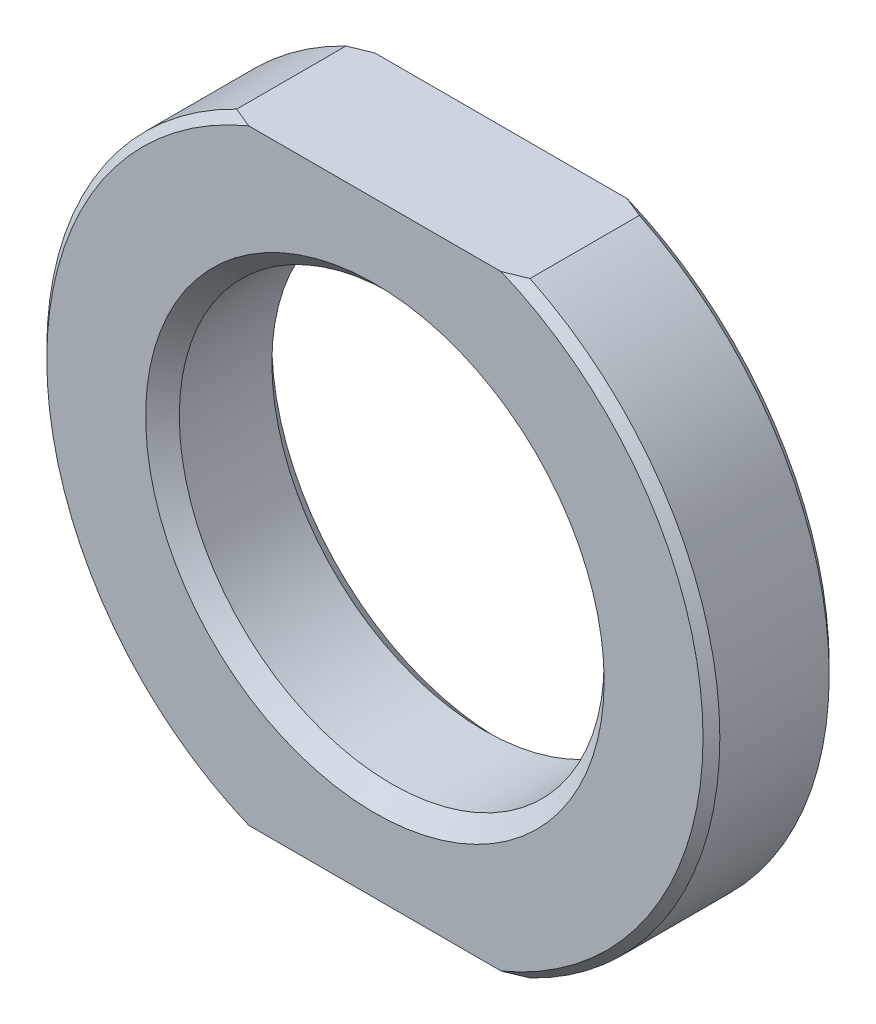
SolidWorks part; units mm, degrees
ref_plane "Płaszczyzna przednia" through (0, 0, 0) normal (0, 0, 1) x (1, 0, 0)
ref_plane "Płaszczyzna górna" through (0, 0, 0) normal (0, 1, 0) x (1, 0, 0)
ref_plane "Płaszczyzna prawa" through (0, 0, 0) normal (1, 0, 0) x (0, 0, -1)
sketch "Szkic1" plane through (0, 0, 0) normal (0, 0, 1) x (1, 0, 0)
  circle A0 centre (0, 0) radius 40
  dimension "D1" = 80
extrude "Dodanie-wyciągnięcie1" add sketch "Szkic1" along normal blind 15
hole_wizard "Otwór gwintowany M561" positions "Szkic3" profile "Szkic2" tap size "M56" standard "ISO" end condition up to next
sketch "Szkic3" plane through (0, 0, 15) normal (0, 0, 1) x (1, 0, 0)
  point P0 (0, 0)
sketch "Szkic2" plane through (0, 0, 15) normal (1, 0, 0) x (0, -1, 0)
  line L0 (0, 0) -> (0, 15)
  line L1 (0, 15) -> (25.25, 15)
  line L2 (25.25, 15) -> (25.25, 0)
  line L5 (25.25, 0) -> (0, 0)
  line L11 (0, -6.35) -> (0, 107.95) construction
  dimension "Średnica otworu gwintowanego na wylot" = 50.5
  dimension "Głębokość otworu gwintowanego na wylot" = 15
cosmetic thread "Gwint otworu1" parameters "D2"=56
chamfer "Sfazowanie1" distance 2 angle 45 2 edges at (25.25, 0, 0) (25.25, 0, 15)
chamfer "Sfazowanie2" distance 1 angle 45 2 edges at (40, 0, 15) (40, 0, 0)
sketch "Szkic4" plane through (0, 0, 15) normal (0, 0, 1) x (1, 0, 0)
  line L0 (0, 0) -> (-73.063, 0) construction
  line L1 (36.2408, -47.1113) -> (36.2408, -36)
  line L2 (-45.0264, 47.1113) -> (36.2408, 47.1113)
  line L3 (-45.0264, 47.1113) -> (-45.0264, 36)
  line L4 (-45.0264, 36) -> (36.2408, 36)
  line L5 (36.2408, 47.1113) -> (36.2408, 36)
  line L6 (-45.0264, -36) -> (36.2408, -36)
  line L7 (-45.0264, -47.1113) -> (-45.0264, -36)
  line L8 (-45.0264, -47.1113) -> (36.2408, -47.1113)
  dimension "D1" = 72
extrude "Wytnij-wyciągnięcie1" cut sketch "Szkic4" against normal up to next
